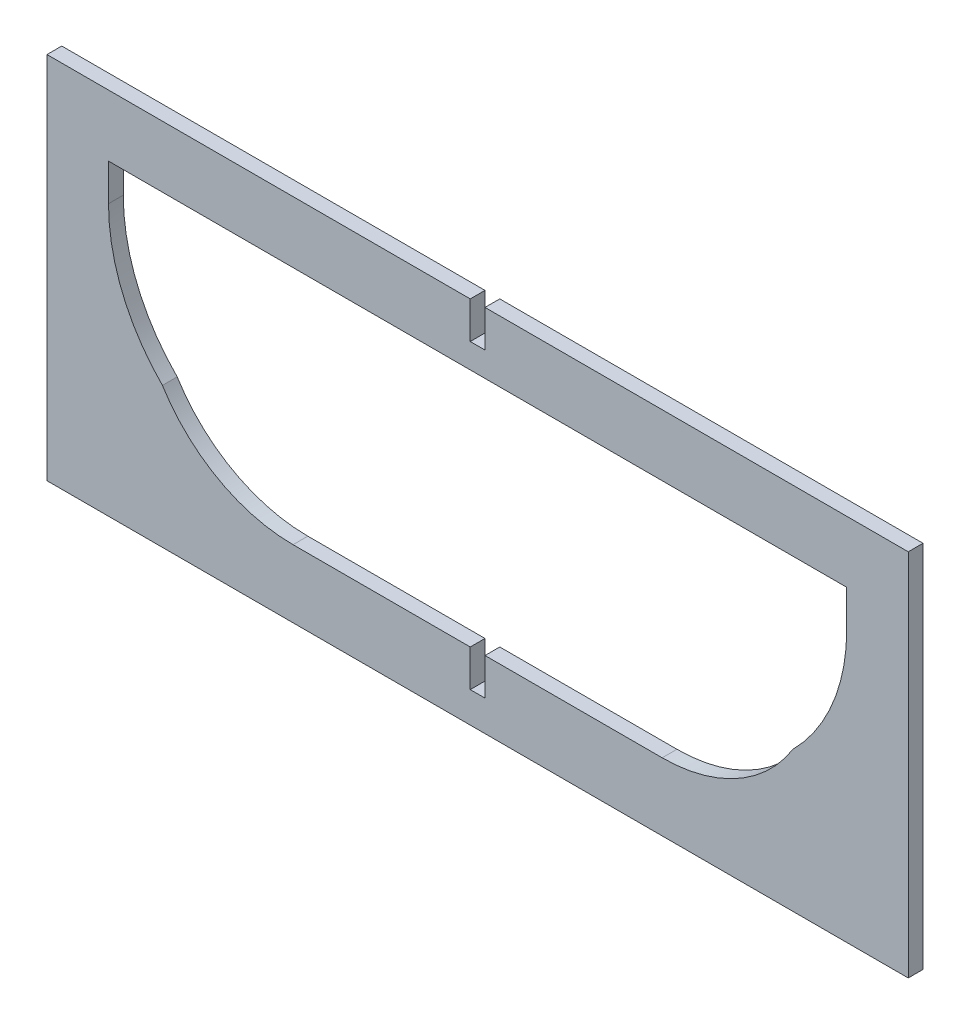
SolidWorks part; units mm, degrees
ref_plane "Front" through (0, 0, 0) normal (0, 0, 1) x (1, 0, 0)
ref_plane "Top" through (0, 0, 0) normal (0, 1, 0) x (1, 0, 0)
ref_plane "Right" through (0, 0, 0) normal (1, 0, 0) x (0, 0, -1)
sketch "Sketch1" plane through (0, 0, 0) normal (0, 0, 1) x (1, 0, 0)
  line L1 (0, 0) -> (-200, 0)
  line L2 (0, 0) -> (0, 150)
  line L4 (-200, 0) -> (-200, 150)
  line L5 (-100, 90) -> (-100, 0) construction
  line L6 (-175, 110) -> (-175, 125)
  line L7 (-25, 110) -> (-25, 125)
  line L9 (-175, 125) -> (-25, 125)
  line L11 (-200, 150) -> (0, 150)
  arc A0 (-153.0972, 57.0313) -> (-46.9028, 57.0312) centre (-100, 90) ccw
  arc A1 (-175, 110) -> (-153.0972, 57.0313) centre (-100, 110) ccw
  arc A2 (-46.9028, 57.0312) -> (-25, 110) centre (-100, 110) ccw
  point P6 (0, 0)
  point P16 (0, 0)
  point P17 (0, 0)
  dimension "D3" = 62.5
  dimension "D4" = 75
  dimension "D1" = 200
  dimension "D2" = 25
  dimension "D5" = 20
  dimension "D6" = 90
  dimension "D7" = 150
extrude "Boss-Extrude1" add sketch "Sketch1" along normal blind 6
sketch "Sketch3" plane through (0, 0, 6) normal (0, 0, 1) x (1, 0, 0)
  line L0 (-200, 150) -> (-200, 0) construction
  line L1 (-100, 27.5) -> (-200, 27.5)
  line L2 (-100, 27.5) -> (-100, 125)
  line L3 (-100, 125) -> (-200, 125)
  line L4 (-200, 27.5) -> (-200, 125)
  line L7 (-25, 125) -> (-175, 125) construction
  arc A0 (-153.0972, 57.0313) -> (-46.9028, 57.0312) centre (-100, 90) ccw construction
extrude "Cut-Extrude1" cut sketch "Sketch3" against normal blind 6
sketch "Sketch4" plane through (0, 0, 6) normal (0, 0, 1) x (1, 0, 0)
  line L0 (-250, 110) -> (-100, 110) construction
  line L1 (-100, 90) -> (-250, 90) construction
  line L2 (-250, 90) -> (-250, 110) construction
  line L3 (-25, 125) -> (0, 125) construction
  line L4 (-200, 27.5) -> (-250, 27.5)
  line L5 (-200, 27.5) -> (-200, 0)
  line L6 (-200, 0) -> (-350, 0)
  line L9 (-350, 0) -> (-350, 150)
  line L11 (-325, 110) -> (-325, 125)
  line L12 (-200, 125) -> (-325, 125)
  line L13 (-200, 125) -> (-200, 150)
  line L14 (-200, 150) -> (-350, 150)
  line L16 (0, 0) -> (0, 150) construction
  line L17 (-325, 125) -> (-350, 125) construction
  line L18 (-200, 0) -> (0, 0) construction
  arc A0 (-325, 110) -> (-303.0972, 57.0312) centre (-250, 110) ccw
  circle A1 centre (-100, 90) radius 62.5 construction
  circle A2 centre (-100, 110) radius 75 construction
  arc A3 (-46.9028, 57.0312) -> (-25, 110) centre (-100, 110) ccw construction
  arc A4 (-100, 27.5) -> (-46.9028, 57.0312) centre (-100, 90) ccw construction
  arc A5 (-303.0972, 57.0312) -> (-250, 27.5) centre (-250, 90) ccw
  point P20 (-350, 1.6583)
  point P36 (-200, 125)
  point P38 (-200, 150)
  point P40 (-25, 125)
  point P42 (0, 0)
  point P43 (0, 0)
  dimension "D1" = 150
  dimension "D2" = 125
  dimension "D4" = 125
  dimension "D3" = 150
extrude "Boss-Extrude3" add sketch "Sketch4" against normal blind 6
sketch "Sketch5" plane through (0, 0, 6) normal (0, 0, 1) x (1, 0, 0)
  line L1 (-178, 150) -> (-172, 150)
  line L2 (-178, 150) -> (-178, 135)
  line L3 (-178, 135) -> (-172, 135)
  line L4 (-172, 150) -> (-172, 135)
  line L5 (-250, 27.5) -> (-100, 27.5) construction
  line L6 (-178, 27.5) -> (-172, 27.5)
  line L7 (-178, 27.5) -> (-178, 12.5)
  line L8 (-178, 12.5) -> (-172, 12.5)
  line L9 (-172, 27.5) -> (-172, 12.5)
  line L10 (0, 150) -> (-350, 150) construction
  point P4 (-177.5407, 147.9373)
  point P12 (-175, 150)
  point P14 (-175, 150)
  dimension "D1" = 6
  dimension "D2" = 15
extrude "Cut-Extrude2" cut sketch "Sketch5" against normal blind 6
